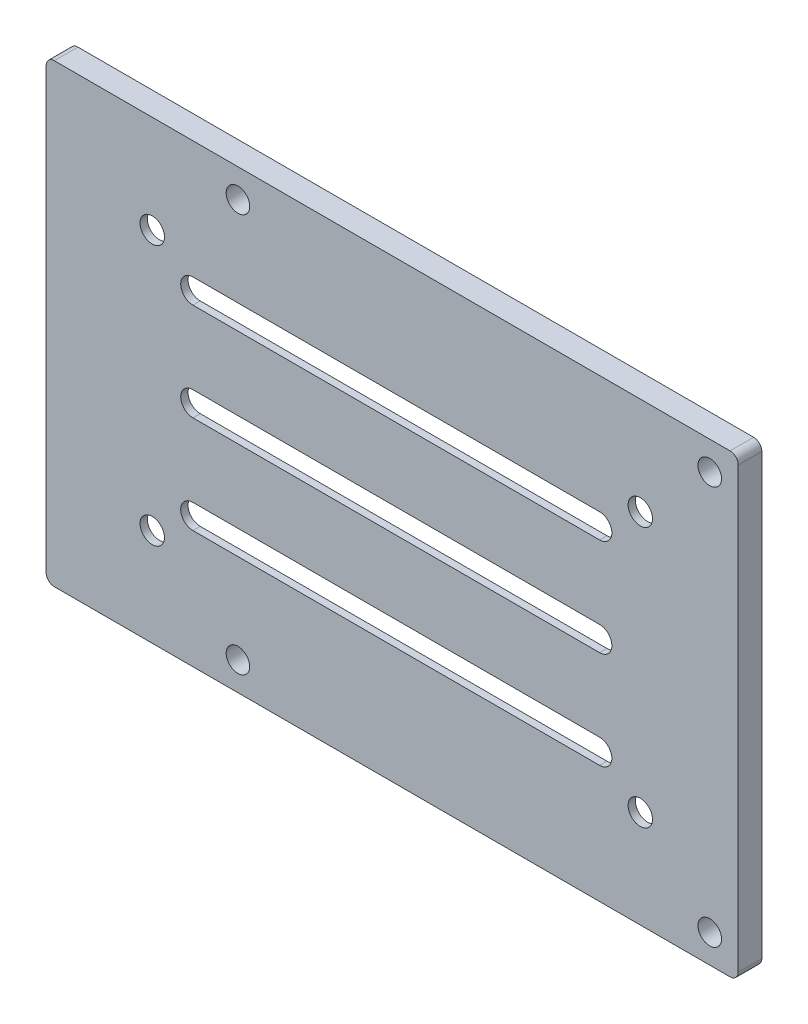
SolidWorks part; units mm, degrees
ref_plane "Front Plane" through (0, 0, 0) normal (0, 0, 1) x (1, 0, 0)
ref_plane "Top Plane" through (0, 0, 0) normal (0, 1, 0) x (1, 0, 0)
ref_plane "Right Plane" through (0, 0, 0) normal (1, 0, 0) x (0, 0, -1)
sketch "Sketch1" plane through (0, 0, 0) normal (0, 0, 1) x (1, 0, 0)
  line L4 (0, -47.5) -> (0, 75.1224) construction
  line L5 (-53.5, -47.5) -> (53.5, -47.5) construction
  line L6 (-53.5, -47.5) -> (-53.5, 47.5) construction
  line L7 (-53.5, 47.5) -> (-45.802, 47.5) construction
  line L8 (53.5, -47.5) -> (53.5, 47.5) construction
  line L9 (-53.5, -47.5) -> (53.5, 47.5) construction
  line L10 (-53.5, 47.5) -> (53.5, -47.5) construction
  line L11 (0, 0) -> (92.3064, 0) construction
  line L12 (48, 57.5289) -> (48, -67.5733) construction
  line L13 (-48, 56.5105) -> (-48, -72.884) construction
  line L14 (-42, -16.4523) -> (43, -16.4523) construction
  line L15 (39.5367, -54.9766) -> (39.5367, 8.0477) construction
  line L16 (43.0367, 11.5477) -> (-42.0367, 11.5477) construction
  line L17 (43.0367, 11.5477) -> (43.0367, -44.4523) construction
  line L18 (43.0367, -44.4523) -> (-42.0367, -44.4523) construction
  line L19 (-42.0367, 11.5477) -> (-42.0367, -44.4523) construction
  line L20 (43.0367, 11.5477) -> (-42.0367, -44.4523) construction
  line L21 (43.0367, -44.4523) -> (-42.0367, 11.5477) construction
  line L22 (39.5367, -40.9523) -> (-18.4633, -40.9523) construction
  line L23 (39.5367, 8.0477) -> (-18.4633, 8.0477) construction
  line L24 (45.802, 47.5) -> (53.5, 47.5) construction
  line L26 (45.802, 47.5) -> (45.802, 62.5) construction
  line L27 (45.802, 62.5) -> (-45.802, 62.5) construction
  line L28 (-45.802, 47.5) -> (-45.802, 62.5) construction
  line L29 (45.802, 16.5583) -> (-45.802, 62.5) construction
  line L30 (45.802, 62.5) -> (-45.802, 16.5583) construction
  line L32 (43.0367, 11.5477) -> (-42.0367, 11.5477)
  line L33 (43.0367, 11.5477) -> (43.0367, -44.4523)
  line L34 (43.0367, -44.4523) -> (-42.0367, -44.4523)
  line L35 (-42.0367, 11.5477) -> (-42.0367, -44.4523)
  circle A0 centre (39.5367, -40.9523) radius 1.45 construction
  circle A1 centre (39.5367, 8.0477) radius 1.45 construction
  circle A2 centre (-18.4633, -40.9523) radius 1.45 construction
  circle A3 centre (-18.4633, 8.0477) radius 1.45 construction
  circle A4 centre (39.5367, 8.0477) radius 1.45
  circle A5 centre (39.5367, -40.9523) radius 1.45
  circle A6 centre (-18.4633, 8.0477) radius 1.45
  circle A7 centre (-18.4633, -40.9523) radius 1.4444
  point P0 (0, 0)
  point P12 (0.5, -16.4523)
  point P15 (0.5, -16.4523)
  point P31 (0, -47.5)
  point P32 (0, 39.5291)
  dimension "D3" = 5.5
  dimension "D10" = 2.9
  dimension "D11" = 2.9
  dimension "D13" = 2.9
  dimension "D14" = 2.9
  dimension "D1" = 107
  dimension "D2" = 95
  dimension "D4" = 5.5
  dimension "D5" = 85
  dimension "D6" = 56
  dimension "D7" = 3.5
  dimension "D8" = 3.5
  dimension "D9" = 49
  dimension "D12" = 58
  dimension "D15" = 58
  dimension "D16" = 0.5
  dimension "D17" = 15
extrude "Boss-Extrude2" add sketch "Sketch1" along normal blind 2.9
fillet "Fillet1" radius 1 4 edges at (-42.0367, 11.5477, 1.45) (43.0367, 11.5477, 1.45) (-42.0367, -44.4523, 1.45) (43.0367, -44.4523, 1.45)
sketch "Sketch2" plane through (0, 0, 0) normal (0, 0, -1) x (-1, 0, 0)
  line L0 (-43.0367, -43.4523) -> (-43.0367, 10.5477) construction
  line L1 (-38.0367, 4.5477) -> (36.0367, 4.5477)
  line L2 (-38.0367, 4.5477) -> (-38.0367, -37.4523)
  line L3 (-38.0367, -37.4523) -> (36.0367, -37.4523)
  line L4 (36.0367, 4.5477) -> (36.0367, -37.4523)
  line L5 (42.0367, 10.5477) -> (42.0367, -43.4523) construction
  line L6 (-42.0367, 11.5477) -> (41.0367, 11.5477) construction
  line L7 (41.0367, -44.4523) -> (-42.0367, -44.4523) construction
  dimension "D1" = 5
  dimension "D2" = 6
  dimension "D3" = 7
  dimension "D4" = 7
extrude "Cut-Extrude1" cut sketch "Sketch2" against normal blind 2
sketch "Sketch3" plane through (0, 0, 2) normal (0, 0, -1) x (-1, 0, 0)
  line L0 (-38.0367, -16.4523) -> (30.9328, -16.4523) construction
  line L2 (-1, -37.4523) -> (-1, -9.9796) construction
  line L3 (-38.0367, -37.4523) -> (36.0367, -37.4523) construction
  line L4 (-38.0367, 4.5477) -> (-38.0367, -37.4523) construction
  line L5 (-26, -4.4523) -> (24, -4.4523) construction
  line L6 (-26, -2.9523) -> (24, -2.9523)
  line L7 (-26, -5.9523) -> (24, -5.9523)
  line L8 (-26, -28.4523) -> (24, -28.4523) construction
  line L9 (-26, -29.9523) -> (24, -29.9523)
  line L10 (-26, -26.9523) -> (24, -26.9523)
  line L11 (-26, -16.4523) -> (24, -16.4523) construction
  line L12 (-26, -14.9523) -> (24, -14.9523)
  line L13 (-26, -17.9523) -> (24, -17.9523)
  line L14 (-26, -5.9523) -> (-26, -14.9523) construction
  line L15 (24, -5.9523) -> (24, -14.9523) construction
  circle A0 centre (-31, -0.4523) radius 1.5
  circle A1 centre (-31, -32.4523) radius 1.5
  circle A2 centre (29, -32.4523) radius 1.5
  circle A3 centre (29, -0.4523) radius 1.5
  arc A4 (-26, -2.9523) -> (-26, -5.9523) centre (-26, -4.4523) ccw
  arc A5 (24, -5.9523) -> (24, -2.9523) centre (24, -4.4523) ccw
  arc A6 (-26, -29.9523) -> (-26, -26.9523) centre (-26, -28.4523) cw
  arc A7 (24, -26.9523) -> (24, -29.9523) centre (24, -28.4523) cw
  arc A8 (-26, -14.9523) -> (-26, -17.9523) centre (-26, -16.4523) ccw
  arc A9 (24, -17.9523) -> (24, -14.9523) centre (24, -16.4523) ccw
  point P18 (-1, -4.4523)
  point P23 (-1, -16.4523)
  point P26 (-1, -28.4523)
  dimension "D3" = 3
  dimension "D6" = 25
  dimension "D1" = 16
  dimension "D2" = 30
  dimension "D4" = 3
  dimension "D5" = 12
  dimension "D7" = 3
extrude "Cut-Extrude2" cut sketch "Sketch3" against normal blind 13
